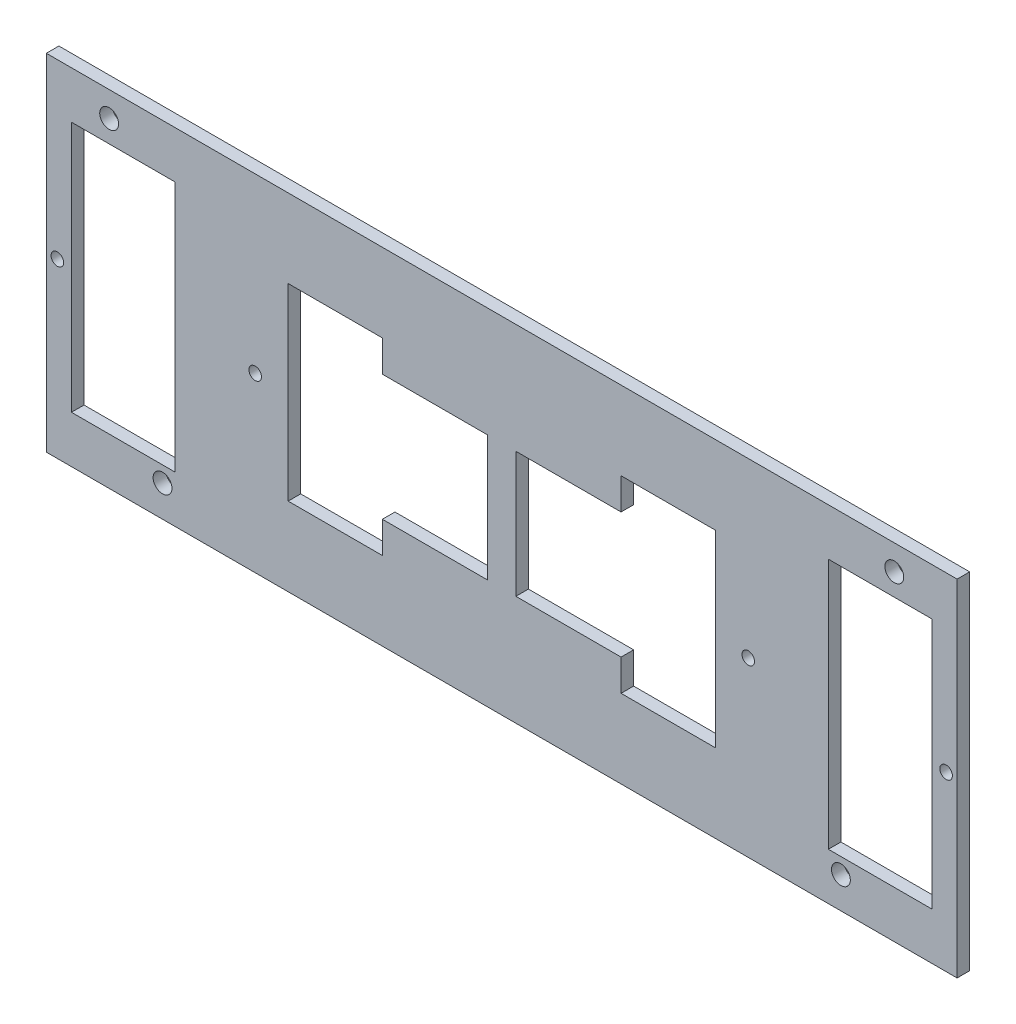
SolidWorks part; units mm, degrees
ref_plane "Front Plane" through (0, 0, 0) normal (0, 0, 1) x (1, 0, 0)
ref_plane "Top Plane" through (0, 0, 0) normal (0, 1, 0) x (1, 0, 0)
ref_plane "Right Plane" through (0, 0, 0) normal (1, 0, 0) x (0, 0, -1)
sketch "Sketch1" plane through (0, 0, 0) normal (0, 0, 1) x (1, 0, 0)
  line L0 (-145, -20.6351) -> (-145, -55)
  line L1 (-145, 55) -> (145, 55)
  line L2 (-145, 55) -> (-145, 40)
  line L3 (-145, -55) -> (145, -55)
  line L4 (145, 55) -> (145, 40)
  line L5 (-145, 55) -> (145, -55) construction
  line L6 (-145, -55) -> (145, 55) construction
  line L7 (-137, 40) -> (-104, 40)
  line L8 (0, -20) -> (0, -55) construction
  line L9 (-137, -40) -> (-104, -40)
  line L10 (-104, 40) -> (-104, -40)
  line L11 (-68, -30) -> (-38, -30)
  line L12 (-68, -30) -> (-68, 30)
  line L13 (-68, 30) -> (-38, 30)
  line L14 (-38, -30) -> (-38, -20)
  line L15 (-38, 20) -> (-38, 30)
  line L16 (-38, -20) -> (-4.5, -20)
  line L17 (38, 20) -> (38, 30)
  line L18 (-38, 20) -> (-4.5, 20)
  line L19 (145, -20.6351) -> (145, -55)
  line L20 (38, -30) -> (38, -20)
  line L21 (68, 30) -> (38, 30)
  line L22 (68, -30) -> (68, 30)
  line L23 (68, -30) -> (38, -30)
  line L24 (145, -20.6351) -> (145, 40)
  line L26 (104, -40) -> (137, -40)
  line L27 (4.5, 20) -> (38, 20)
  line L28 (104, -40) -> (104, 40)
  line L29 (-4.5, -20) -> (-4.5, 20)
  line L30 (4.5, -20) -> (38, -20)
  line L31 (4.5, -20) -> (4.5, 20)
  line L32 (104, 40) -> (137, 40)
  line L33 (-145, 40) -> (-145, -20.6351)
  line L34 (137, -40) -> (137, 40)
  line L35 (-137, 40) -> (-137, -40)
  circle A0 centre (-108, -45) radius 3
  circle A1 centre (-125, 47) radius 3
  circle A2 centre (125, 47) radius 3
  circle A3 centre (108, -45) radius 3
  point P0 (0, 0)
  point P14 (-104, 0)
  point P15 (-68, 0)
  dimension "D10" = 6
  dimension "D13" = 6
  dimension "D15" = 10
  dimension "D1" = 290
  dimension "D2" = 110
  dimension "D4" = 15
  dimension "D5" = 80
  dimension "D6" = 60
  dimension "D7" = 30
  dimension "D8" = 38
  dimension "D9" = 40
  dimension "D11" = 20
  dimension "D12" = 7
  dimension "D14" = 37
  dimension "D16" = 10
  dimension "D17" = 9
  dimension "D18" = 8
  dimension "D19" = 33
  dimension "D20" = 33
  dimension "D21" = 80
  dimension "D22" = 15
  dimension "D23" = 8
extrude "Boss-Extrude1" add sketch "Sketch1" along normal blind 4
sketch "Sketch4" plane through (0, 0, 0) normal (0, 0, -1) x (-1, 0, 0)
  line L0 (145, -55) -> (-145, -55) construction
  line L1 (-145, -55) -> (-145, 55) construction
  circle A0 centre (-141.5, 0) radius 2 construction
  circle A1 centre (-141.5, 0) radius 2 construction
  circle A2 centre (-141.5, 0) radius 2
  dimension "D1" = 4
  dimension "D2" = 55
  dimension "D3" = 3.5
extrude "Cut-Extrude2" cut sketch "Sketch4" against normal blind 10
sketch "Sketch5" plane through (0, 0, 0) normal (0, 0, -1) x (-1, 0, 0)
  circle A0 centre (-78.5, 0) radius 2 construction
  circle A1 centre (-78.5, 0) radius 2
extrude "Cut-Extrude3" cut sketch "Sketch5" against normal blind 10
ref_plane "Plane1" through (0, 0, 0) normal (-1, 0, 0) x (0, 0, 1)
mirror "Mirror1" about plane through (0, 0, 0) normal (-1, 0, 0) of "Cut-Extrude2", "Cut-Extrude3"
